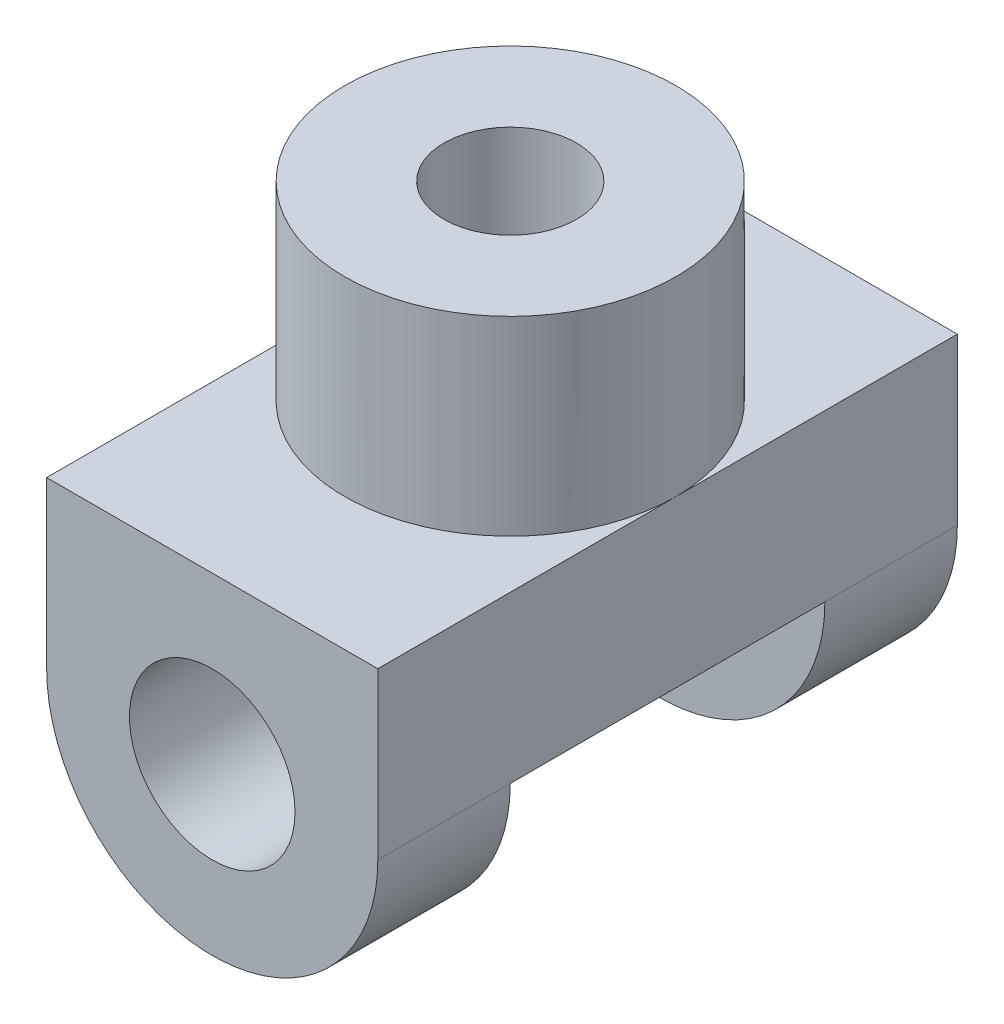
SolidWorks part; units mm, degrees
ref_plane "Front Plane" through (0, 0, 0) normal (0, 0, 1) x (1, 0, 0)
ref_plane "Top Plane" through (0, 0, 0) normal (0, 1, 0) x (1, 0, 0)
ref_plane "Right Plane" through (0, 0, 0) normal (1, 0, 0) x (0, 0, -1)
sketch "Sketch1" plane through (0, 0, 0) normal (0, 1, 0) x (1, 0, 0)
  line L1 (-508, -889) -> (508, -889)
  line L2 (-508, -889) -> (-508, 889)
  line L3 (-508, 889) -> (508, 889)
  line L4 (508, -889) -> (508, 889)
  line L5 (-508, -889) -> (508, 889) construction
  line L6 (-508, 889) -> (508, -889) construction
  point P0 (0, 0)
  dimension "D1" = 1778
  dimension "D2" = 1016
extrude "Boss-Extrude1" add sketch "Sketch1" along normal blind 508
sketch "Sketch2" plane through (0, 508, 0) normal (0, 1, 0) x (1, 0, 0)
  line L2 (-508, -889) -> (508, -889) construction
  circle A1 centre (0, 25.4) radius 508
  circle A2 centre (0, 25.4) radius 203.2
  dimension "D1" = 914.4
extrude "Boss-Extrude2" add sketch "Sketch2" along normal blind 584.2
sketch "Sketch3" plane through (0, 0, 889) normal (0, 0, 1) x (1, 0, 0)
  line L3 (508, 0) -> (-508, 0)
  circle A2 centre (0, 0) radius 508
  circle A3 centre (0, 0) radius 254
extrude "Boss-Extrude3" add sketch "Sketch3" against normal blind 406.4 contours A2
sketch "Sketch5" plane through (0, 0, 889) normal (0, 0, 1) x (1, 0, 0)
  circle A0 centre (0, 0) radius 254
extrude "Cut-Extrude1" cut sketch "Sketch5" against normal up to next
mirror "Mirror1" about plane through (0, 0, 0) normal (0, 0, 1) of "Cut-Extrude1", "Boss-Extrude3"
